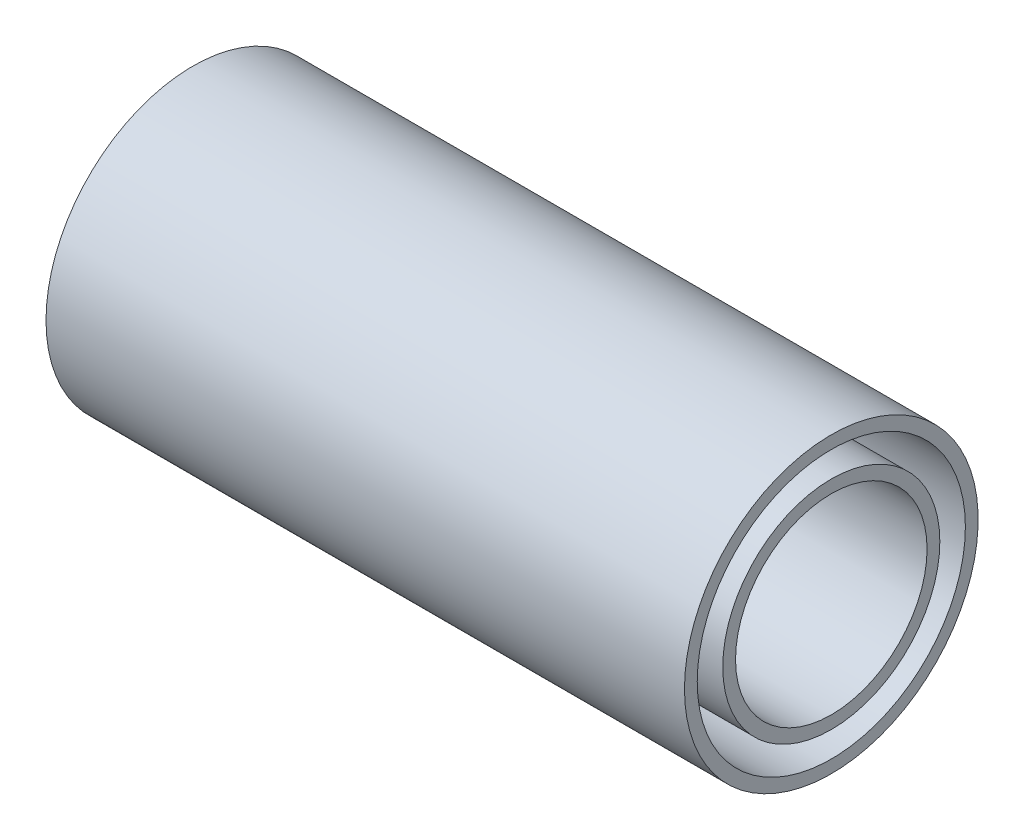
SolidWorks part; units mm, degrees
ref_plane "Front Plane" through (0, 0, 0) normal (0, 0, 1) x (1, 0, 0)
ref_plane "Top Plane" through (0, 0, 0) normal (0, 1, 0) x (1, 0, 0)
ref_plane "Right Plane" through (0, 0, 0) normal (1, 0, 0) x (0, 0, -1)
sketch "Sketch1" plane through (0, 0, 0) normal (0, 0, 1) x (1, 0, 0)
  line L0 (0, 0) -> (30.418, 0)
  line L1 (0, 19.05) -> (127, 19.05)
  line L2 (0, 19.05) -> (0, 21.59)
  line L3 (0, 21.59) -> (127, 21.59)
  line L4 (127, 21.59) -> (127, 19.05)
  line L5 (0, 26.67) -> (127, 26.67)
  line L6 (127, 26.67) -> (127, 29.21)
  line L7 (127, 29.21) -> (0, 29.21)
  line L8 (0, 29.21) -> (0, 26.67)
  dimension "D1" = 2.54
  dimension "D2" = 2.54
  dimension "D3" = 127
  dimension "D4" = 127
  dimension "D5" = 5.08
  dimension "D6" = 19.05
revolve "Revolve1" add sketch "Sketch1" angle 360 about L0
